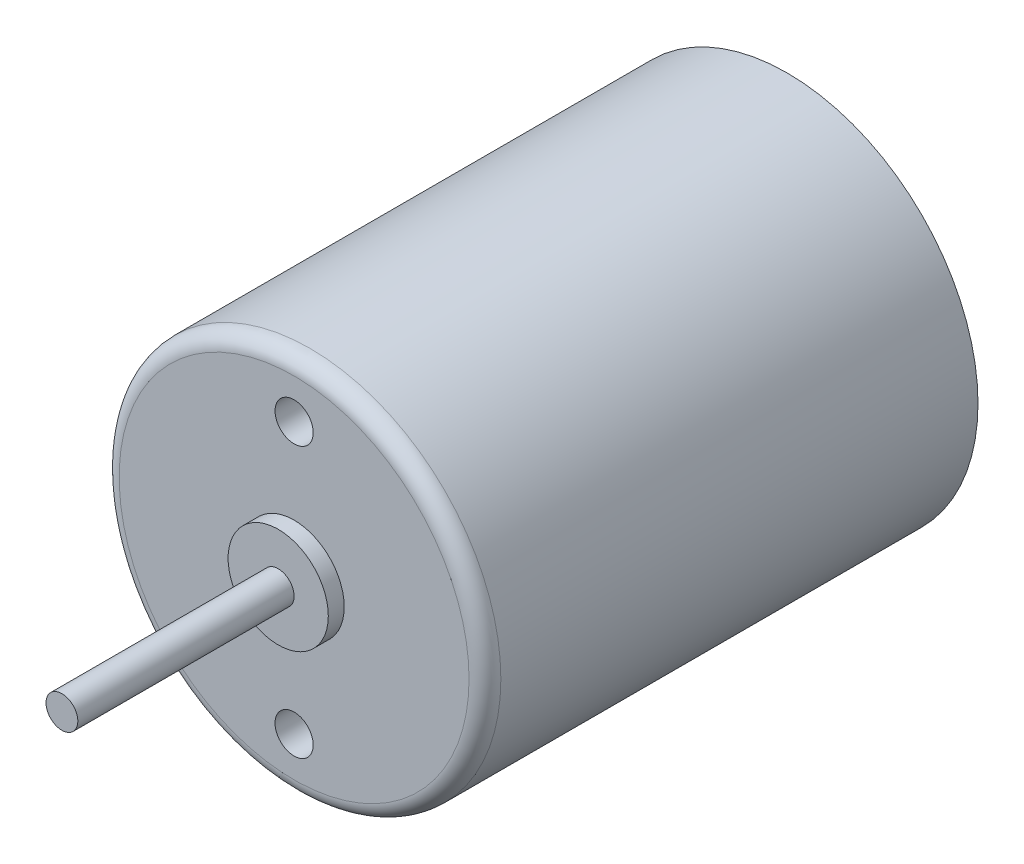
SolidWorks part; units mm, degrees
ref_plane "Front Plane" through (0, 0, 0) normal (0, 0, 1) x (1, 0, 0)
ref_plane "Top Plane" through (0, 0, 0) normal (0, 1, 0) x (1, 0, 0)
ref_plane "Right Plane" through (0, 0, 0) normal (1, 0, 0) x (0, 0, -1)
sketch "Sketch1" plane through (0, 0, 0) normal (0, 0, 1) x (1, 0, 0)
  circle A0 centre (0, 0) radius 12
  dimension "D1" = 24
extrude "Boss-Extrude1" add sketch "Sketch1" along normal blind 31
fillet "Fillet1" radius 1 1 edges at (12, 0, 31)
sketch "Sketch2" plane through (0, 0, 31) normal (0, 0, 1) x (1, 0, 0)
  circle A0 centre (0, 0) radius 3.15
  dimension "D1" = 6.3
extrude "Boss-Extrude2" add sketch "Sketch2" along normal blind 1 contours A0
sketch "Sketch4" plane through (0, 0, 0) normal (0, 0, -1) x (-1, 0, 0)
  circle A0 centre (0, 0) radius 1
  dimension "D1" = 2
extrude "Boss-Extrude3" add sketch "Sketch4" against normal blind 45.6
sketch "Sketch5" plane through (0, 0, 31) normal (0, 0, 1) x (1, 0, 0)
  circle A0 centre (0, -8.5) radius 1.2
  point P2 (0, 0)
  dimension "D1" = 2.4
  dimension "D2" = 8.5
extrude "Cut-Extrude1" cut sketch "Sketch5" against normal blind 3
mirror "Mirror1" about plane through (0, 0, 0) normal (0, 1, 0) of "Cut-Extrude1"
